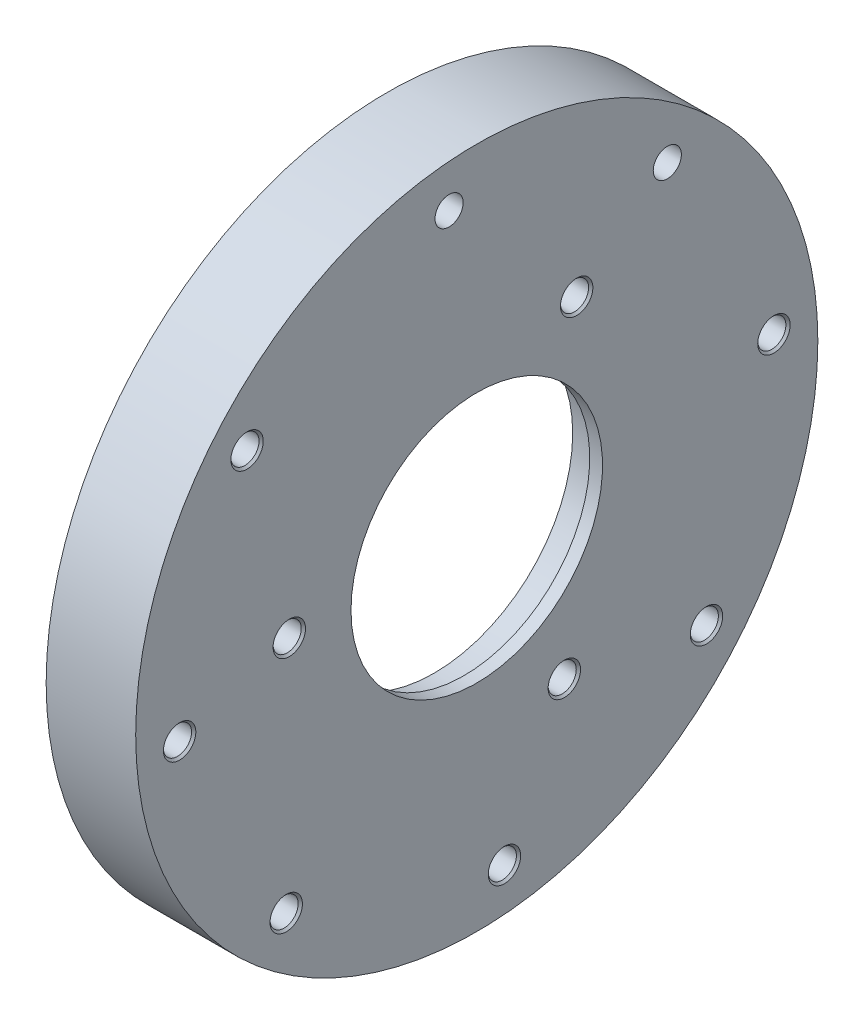
SolidWorks part; units mm, degrees
ref_plane "Front Plane" through (0, 0, 0) normal (0, 0, 1) x (1, 0, 0)
ref_plane "Top Plane" through (0, 0, 0) normal (0, 1, 0) x (1, 0, 0)
ref_plane "Right Plane" through (0, 0, 0) normal (1, 0, 0) x (0, 0, -1)
sketch "Sketch2" plane through (0, 0, 0) normal (0, 0, 1) x (1, 0, 0)
  line L0 (0, 0) -> (80.4799, 0) construction
  line L1 (0, 80) -> (0, 52.5)
  line L2 (0, 52.5) -> (11, 52.5)
  line L3 (11, 52.5) -> (11, 32.5)
  line L4 (11, 32.5) -> (18, 32.5)
  line L5 (18, 32.5) -> (18, 29.5)
  line L6 (18, 29.5) -> (21, 29.5)
  line L7 (21, 29.5) -> (21, 80)
  line L8 (21, 80) -> (0, 80)
  dimension "D1" = 80
  dimension "D2" = 32.5
  dimension "D3" = 52.5
  dimension "D4" = 18
  dimension "D5" = 3
  dimension "D6" = 7
  dimension "D7" = 3
revolve "Revolve1" add sketch "Sketch2" angle 360 about L0
sketch "Sketch3" plane through (0, 0, 0) normal (-1, 0, 0) x (0, 0, 1)
  circle A0 centre (0, 0) radius 60 construction
  circle A1 centre (0, 60) radius 2.525
  circle A2 centre (12.0779, 58.7718) radius 2.525
  circle A3 centre (23.6614, 55.1375) radius 2.525
  circle A4 centre (34.2761, 49.2458) radius 2.525
  circle A5 centre (43.4876, 41.338) radius 2.525
  circle A6 centre (50.9187, 31.7378) radius 2.525
  circle A7 centre (56.2651, 20.8383) radius 2.525
  circle A8 centre (59.3081, 9.0857) radius 2.525
  circle A9 centre (59.923, -3.039) radius 2.525
  circle A10 centre (58.0846, -15.0392) radius 2.525
  circle A11 centre (53.8683, -26.4236) radius 2.525
  circle A12 centre (47.4465, -36.7264) radius 2.525
  circle A13 centre (39.0823, -45.5255) radius 2.525
  circle A14 centre (29.1181, -52.4608) radius 2.525
  circle A15 centre (17.9618, -57.2484) radius 2.525
  circle A16 centre (6.0701, -59.6922) radius 2.525
  circle A17 centre (-6.0701, -59.6922) radius 2.525
  circle A18 centre (-17.9618, -57.2484) radius 2.525
  circle A19 centre (-29.1181, -52.4608) radius 2.525
  circle A20 centre (-39.0823, -45.5255) radius 2.525
  circle A21 centre (-47.4465, -36.7264) radius 2.525
  circle A22 centre (-53.8683, -26.4236) radius 2.525
  circle A23 centre (-58.0846, -15.0392) radius 2.525
  circle A24 centre (-59.923, -3.039) radius 2.525
  circle A25 centre (-59.3081, 9.0857) radius 2.525
  circle A26 centre (-56.2651, 20.8383) radius 2.525
  circle A27 centre (-50.9187, 31.7378) radius 2.525
  circle A28 centre (-43.4876, 41.338) radius 2.525
  circle A29 centre (-34.2761, 49.2458) radius 2.525
  circle A30 centre (-23.6614, 55.1375) radius 2.525
  circle A31 centre (-12.0779, 58.7718) radius 2.525
  point P67 (0, 0)
  dimension "D1" = 120
  dimension "D2" = 5.05
  dimension "D3" = 31
extrude "Cut-Extrude1" cut sketch "Sketch3" against normal blind 4
sketch "Sketch4" [suppressed] plane through (21, 0, 0) normal (1, 0, 0) x (0, 0, -1)
  circle A0 centre (-38.0255, -58.7712) radius 5.5
  circle A1 centre (-68.4457, -14.6694) radius 5.5
  circle A2 centre (-58.7712, 38.0255) radius 5.5
  circle A3 centre (-14.6694, 68.4457) radius 5.5
  circle A4 centre (38.0255, 58.7712) radius 5.5
  circle A5 centre (68.4457, 14.6694) radius 5.5
  circle A6 centre (58.7712, -38.0255) radius 5.5
  circle A7 centre (14.6694, -68.4457) radius 5.5
  point P16 (0, 0)
  dimension "D2" = 11
  dimension "D1" = 8
extrude "Cut-Extrude2" [suppressed] cut sketch "Sketch4" against normal blind 4
sketch "Sketch5" [suppressed] plane through (21, 0, 0) normal (1, 0, 0) x (0, 0, -1)
  circle A0 centre (-38.0255, -58.7712) radius 3
  circle A1 centre (-68.4457, -14.6694) radius 3
  circle A2 centre (-58.7712, 38.0255) radius 3
  circle A3 centre (-14.6694, 68.4457) radius 3
  circle A4 centre (38.0255, 58.7712) radius 3
  circle A5 centre (68.4457, 14.6694) radius 3
  circle A6 centre (58.7712, -38.0255) radius 3
  circle A7 centre (14.6694, -68.4457) radius 3
  point P16 (0, 0)
  dimension "D2" = 6
  dimension "D1" = 8
extrude "Cut-Extrude3" [suppressed] cut sketch "Sketch5" against normal through all
sketch "Sketch6" plane through (0, 0, 0) normal (-1, 0, 0) x (0, 0, 1)
  circle A0 centre (53.8756, 44.6925) radius 3
  circle A1 centre (69.6982, -6.4934) radius 3
  circle A2 centre (44.6925, -53.8756) radius 3
  circle A3 centre (-6.4934, -69.6982) radius 3
  circle A4 centre (-53.8756, -44.6925) radius 3
  circle A5 centre (-69.6982, 6.4934) radius 3
  circle A6 centre (-44.6925, 53.8756) radius 3
  circle A7 centre (6.4934, 69.6982) radius 3
  point P15 (0, 0)
  dimension "D2" = 6
  dimension "D1" = 8
extrude "Cut-Extrude4" cut sketch "Sketch6" against normal blind 11
sketch "Sketch7" plane through (21, 0, 0) normal (-1, 0, 0) x (0, 0, 1)
  circle A0 centre (53.8756, 44.6925) radius 3.3
  circle A1 centre (69.6982, -6.4934) radius 3.3
  circle A2 centre (44.6925, -53.8756) radius 3.3
  circle A3 centre (-6.4934, -69.6982) radius 3.3
  circle A4 centre (-53.8756, -44.6925) radius 3.3
  circle A5 centre (-69.6982, 6.4934) radius 3.3
  circle A6 centre (-44.6925, 53.8756) radius 3.3
  circle A7 centre (6.4934, 69.6982) radius 3.3
  point P15 (0, 0)
  dimension "D1" = 6.6
  dimension "D2" = 8
extrude "Cut-Extrude5" cut sketch "Sketch7" along normal blind 10
sketch "Sketch8" [suppressed] plane through (21, 0, 0) normal (1, 0, 0) x (0, 0, -1)
  circle A0 centre (-23.7966, 67.4351) radius 1
  dimension "D1" = 2
extrude "Cut-Extrude6" [suppressed] cut sketch "Sketch8" against normal blind 2
sketch "Sketch9" plane through (0, 0, 0) normal (-1, 0, 0) x (0, 0, 1)
  circle A0 centre (2.5177, -71.4663) radius 1
  dimension "D1" = 2
extrude "Cut-Extrude7" cut sketch "Sketch9" against normal blind 2
sketch "Sketch10" plane through (21, 0, 0) normal (1, 0, 0) x (0, 0, -1)
  line L0 (69.6982, 6.4934) -> (-44.6925, -53.8756) construction
  line L1 (23.4319, 37.2417) -> (0, 0) construction
  circle A0 centre (0, 0) radius 44 construction
  circle A1 centre (23.4319, 37.2417) radius 3.3
  circle A2 centre (20.5363, -38.9135) radius 3.3
  circle A3 centre (-43.9682, 1.6717) radius 3.3
  point P15 (0, 0)
  dimension "D1" = 6.6
  dimension "D2" = 88
  dimension "D3" = 30
  dimension "D4" = 3
extrude "Cut-Extrude8" cut sketch "Sketch10" against normal up to next
chamfer "Chamfer1" distance 0.5 angle 45 9 edges at (21, -53.8756, 47.9925) (21, -69.6982, -3.1934) (21, -44.6925, -50.5756) (21, 6.4934, -66.3982) (21, 44.6925, 57.1756) (21, -6.4934, 72.9982) (21, 1.6717, 40.6682) (21, -38.9135, -23.8363) (21, 37.2417, -26.7319)
equation "\"R_ROLL\"= 5mm"
equation "\"D_SUN\"= 120mm"
equation "\"NUM_ROLL\"= 31"
equation "\"RHO\"= 1mm"
equation "\"D_SHAFT\"= 28mm"
equation "\"D_OUTPUT\"= 80mm"
equation "\"NUM_OUT\"= 8"
equation "\"R_OUT_ROLL\"= 5mm"
equation "\"D1@Sketch3\"=\"D_SUN\""
